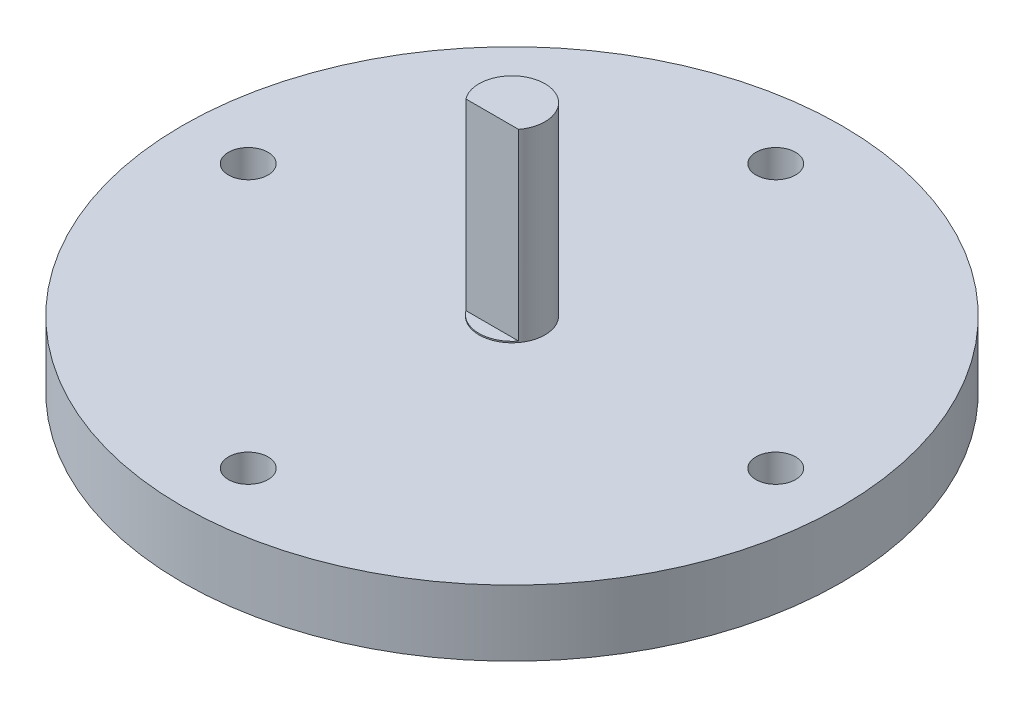
SolidWorks part; units mm, degrees
ref_plane "Front Plane" through (0, 0, 0) normal (0, 0, 1) x (1, 0, 0)
ref_plane "Top Plane" through (0, 0, 0) normal (0, 1, 0) x (1, 0, 0)
ref_plane "Right Plane" through (0, 0, 0) normal (1, 0, 0) x (0, 0, -1)
sketch "Sketch1" plane through (0, 0, 0) normal (0, 1, 0) x (1, 0, 0)
  circle A0 centre (0, 0) radius 25
  circle A2 centre (0, 0) radius 20 construction
  circle A3 centre (0, -20) radius 1.5
  circle A4 centre (-20, 0) radius 1.5
  circle A5 centre (0, 20) radius 1.5
  circle A6 centre (20, 0) radius 1.5
  point P16 (0, 0)
  dimension "D1" = 50
  dimension "D3" = 40
  dimension "D4" = 3
  dimension "D5" = 4
extrude "Boss-Extrude1" add sketch "Sketch1" along normal blind 5
sketch "Sketch2" plane through (0, 5, 0) normal (0, 1, 0) x (1, 0, 0)
  circle A0 centre (0, 0) radius 2.5
  dimension "D1" = 5
extrude "Boss-Extrude2" add sketch "Sketch2" along normal blind 14
sketch "Sketch3" plane through (0, 0, 0) normal (0, -1, 0) x (1, 0, 0)
  circle A0 centre (0, 0) radius 1.5
  dimension "D1" = 3
extrude "Cut-Extrude1" cut sketch "Sketch3" against normal blind 5
sketch "Sketch4" plane through (0, 19, 0) normal (0, 1, 0) x (1, 0, 0)
  line L0 (2, -1.5) -> (-2, -1.5)
  circle A1 centre (0, 0) radius 2.5
  arc A2 (-2, -1.5) -> (2, -1.5) centre (0, 0) ccw
  dimension "D2" = 1.5
  dimension "D1" = 0
extrude "Cut-Extrude3" cut sketch "Sketch4" against normal blind 13.9
